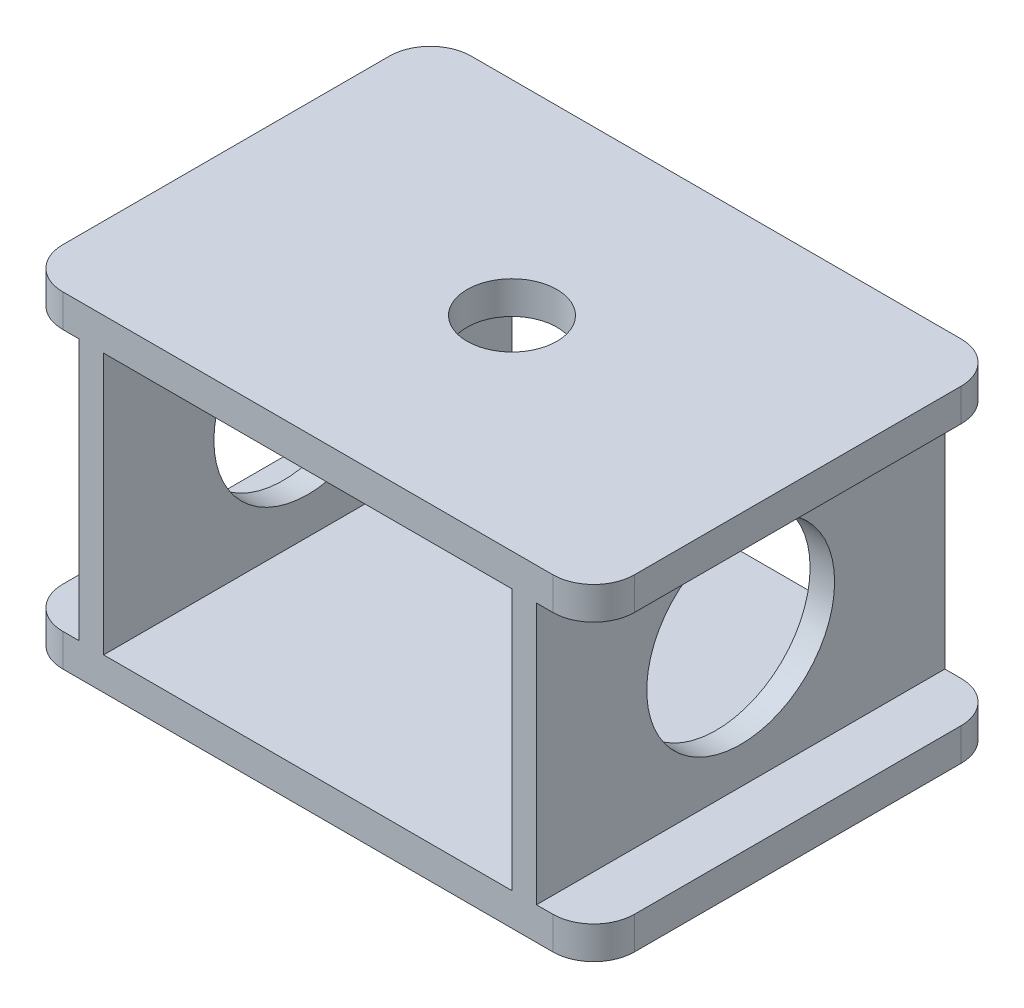
SolidWorks part; units mm, degrees
ref_plane "Front Plane" through (0, 0, 0) normal (0, 0, 1) x (1, 0, 0)
ref_plane "Top Plane" through (0, 0, 0) normal (0, 1, 0) x (1, 0, 0)
ref_plane "Right Plane" through (0, 0, 0) normal (1, 0, 0) x (0, 0, -1)
sketch "Sketch1" plane through (0, 0, 0) normal (0, 1, 0) x (1, 0, 0)
  line L1 (-30, 25) -> (30, 25)
  line L2 (-35, 20) -> (-35, -20)
  line L3 (-30, -25) -> (30, -25)
  line L4 (35, 20) -> (35, -20)
  line L5 (-35, 25) -> (35, -25) construction
  line L6 (-35, -25) -> (35, 25) construction
  arc A0 (30, -25) -> (35, -20) centre (30, -20) ccw
  arc A1 (-35, -20) -> (-30, -25) centre (-30, -20) ccw
  arc A2 (30, 25) -> (35, 20) centre (30, 20) cw
  arc A3 (-30, 25) -> (-35, 20) centre (-30, 20) ccw
  point P0 (17.3661, -3.4004)
  dimension "D3" = 5
  dimension "D1" = 50
  dimension "D2" = 70
extrude "Boss-Extrude1" add sketch "Sketch1" along normal blind 4
sketch "Sketch2" plane through (0, 4, 0) normal (0, 1, 0) x (1, 0, 0)
  line L0 (30, 25) -> (-30, 25) construction
  line L1 (-28, 25) -> (-25, 25)
  line L2 (-28, 25) -> (-28, -25)
  line L3 (-28, -25) -> (-25, -25)
  line L4 (-25, 25) -> (-25, -25)
  line L5 (25, 25) -> (28, 25)
  line L6 (25, 25) -> (25, -25)
  line L7 (25, -25) -> (28, -25)
  line L8 (28, 25) -> (28, -25)
  line L9 (-30, -25) -> (30, -25) construction
  line L10 (0, -2.2) -> (0, 2.2) construction
  dimension "D1" = 25
  dimension "D2" = 25
  dimension "D3" = 3
  dimension "D4" = 3
extrude "Boss-Extrude2" add sketch "Sketch2" along normal blind 32
sketch "Sketch3" plane through (0, 36, 0) normal (0, 1, 0) x (1, 0, 0)
  line L1 (28, -25) -> (30, -25) construction
  line L2 (35, -20) -> (35, 20) construction
  line L3 (30, 25) -> (28, 25) construction
  line L5 (-25, -25) -> (25, -25) construction
  line L7 (25, 25) -> (-25, 25) construction
  line L9 (-28, 25) -> (-30, 25) construction
  line L10 (-35, 20) -> (-35, -20) construction
  line L11 (-30, -25) -> (-28, -25) construction
  line L13 (28, -25) -> (30, -25)
  line L14 (35, -20) -> (35, 20)
  line L15 (30, 25) -> (28, 25)
  line L17 (-25, -25) -> (25, -25)
  line L19 (25, 25) -> (-25, 25)
  line L21 (-28, 25) -> (-30, 25)
  line L22 (-35, 20) -> (-35, -20)
  line L23 (-30, -25) -> (-28, -25)
  line L24 (-28, -25) -> (-25, -25) construction
  line L25 (25, -25) -> (28, -25) construction
  line L26 (28, 25) -> (25, 25) construction
  line L27 (-25, 25) -> (-28, 25) construction
  line L28 (-28, -25) -> (-25, -25)
  line L29 (25, -25) -> (28, -25)
  line L30 (28, 25) -> (25, 25)
  line L31 (-25, 25) -> (-28, 25)
  arc A0 (30, -25) -> (35, -20) centre (30, -20) ccw construction
  arc A1 (35, 20) -> (30, 25) centre (30, 20) ccw construction
  arc A2 (-30, 25) -> (-35, 20) centre (-30, 20) ccw construction
  arc A3 (-35, -20) -> (-30, -25) centre (-30, -20) ccw construction
  arc A4 (30, -25) -> (35, -20) centre (30, -20) ccw
  arc A5 (35, 20) -> (30, 25) centre (30, 20) ccw
  arc A6 (-30, 25) -> (-35, 20) centre (-30, 20) ccw
  arc A7 (-35, -20) -> (-30, -25) centre (-30, -20) ccw
extrude "Boss-Extrude3" add sketch "Sketch3" along normal blind 4
sketch "Sketch4" plane through (28, 0, 0) normal (1, 0, 0) x (0, 0, -1)
  line L0 (27.5, 0) -> (-27.5, 0) construction
  circle A0 centre (0, 20) radius 11.5
  dimension "D1" = 23
  dimension "D2" = 20
extrude "Cut-Extrude1" cut sketch "Sketch4" against normal through all
sketch "Sketch5" plane through (0, 40, 0) normal (0, 1, 0) x (1, 0, 0)
  line L0 (0, -22) -> (0, 22) construction
  line L1 (-22, 0) -> (22, 0) construction
  circle A0 centre (0, 0) radius 5.5
  point P2 (0, 0)
  dimension "D1" = 11
extrude "Cut-Extrude2" cut sketch "Sketch5" against normal up to next
